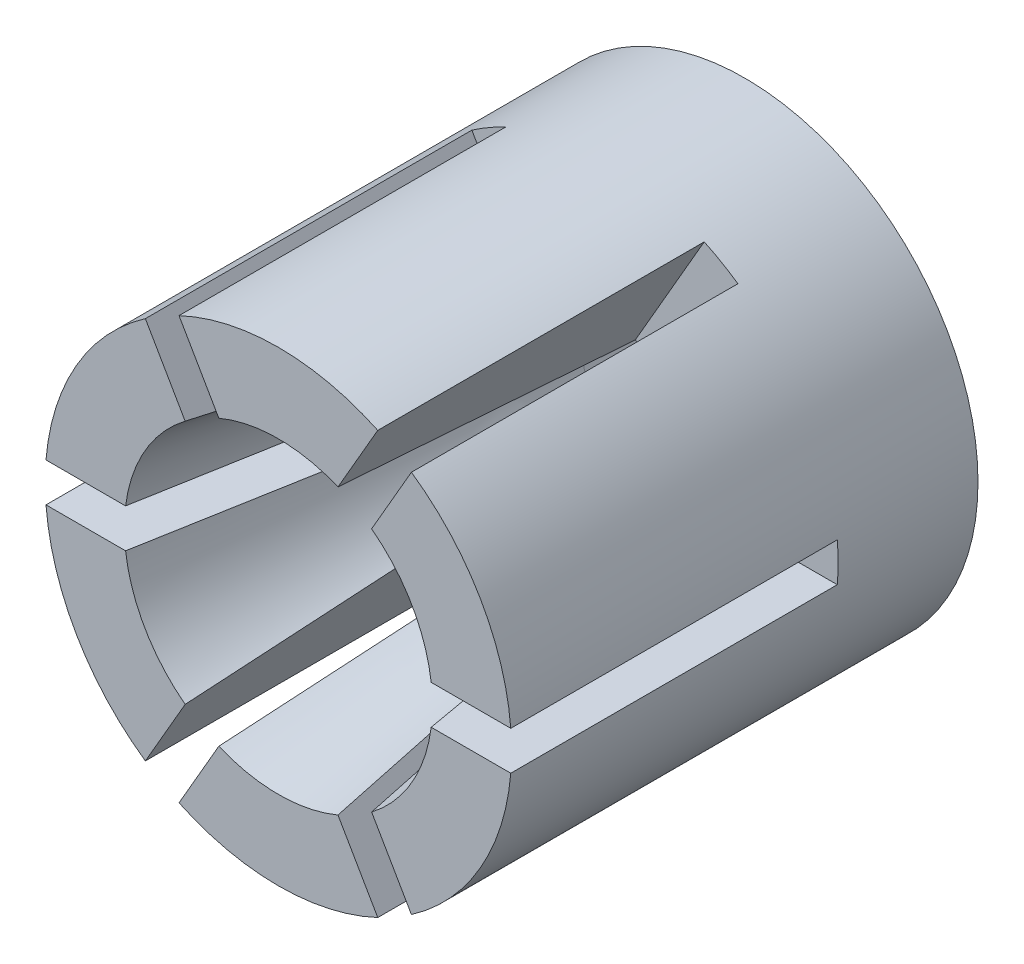
SolidWorks part; units mm, degrees
ref_plane "Front Plane" through (0, 0, 0) normal (0, 0, 1) x (1, 0, 0)
ref_plane "Top Plane" through (0, 0, 0) normal (0, 1, 0) x (1, 0, 0)
ref_plane "Right Plane" through (0, 0, 0) normal (1, 0, 0) x (0, 0, -1)
sketch "Sketch4" plane through (0, 0, 0) normal (1, 0, 0) x (0, 0, -1)
  line L0 (-24.3984, 0) -> (42.9187, 0) construction
  line L2 (0, 0) -> (60, 0)
  line L3 (0, 0) -> (0, 30)
  line L4 (0, 30) -> (60, 30)
  line L5 (60, 0) -> (60, 30)
  dimension "D1" = 60
  dimension "D2" = 60
revolve "Revolve1" add sketch "Sketch4" angle 360 about L0
sketch "Sketch5" plane through (0, 0, 0) normal (1, 0, 0) x (0, 0, -1)
  line L0 (-8.4887, 0) -> (73.4435, 0) construction
  line L1 (0, 0) -> (0, 19.8163)
  line L2 (0, 30) -> (0, -30) construction
  line L3 (0, 19.8163) -> (50, 11)
  line L4 (50, 11) -> (60, 11)
  line L5 (60, -30) -> (60, 30) construction
  line L6 (60, 11) -> (60, 0)
  line L7 (60, 0) -> (0, 0)
  dimension "D1" = 10
  dimension "D2" = 10
  dimension "D3" = 22
revolve "Cut-Revolve1" cut sketch "Sketch5" angle 360 about L0
sketch "Sketch6" plane through (0, 0, 0) normal (1, 0, 0) x (0, 0, -1)
  line L0 (-3.2684, 0) -> (66.8075, 0) construction
  line L1 (0, 30) -> (0, -30) construction
  line L2 (42, 2.5) -> (0, 2.5)
  line L3 (42, 2.5) -> (42, -2.5)
  line L4 (42, -2.5) -> (0, -2.5)
  line L5 (0, 2.5) -> (0, -2.5)
  line L6 (42, 2.5) -> (0, -2.5) construction
  line L7 (42, -2.5) -> (0, 2.5) construction
  point P3 (21, 0)
  dimension "D1" = 5
  dimension "D2" = 42
extrude "Cut-Extrude1" cut sketch "Sketch6" along normal up to next
pattern_circular "CirPattern3" count 6 over 360 about axis through (0, 0, 0) along (0, 0, 1) of "Cut-Extrude1"
